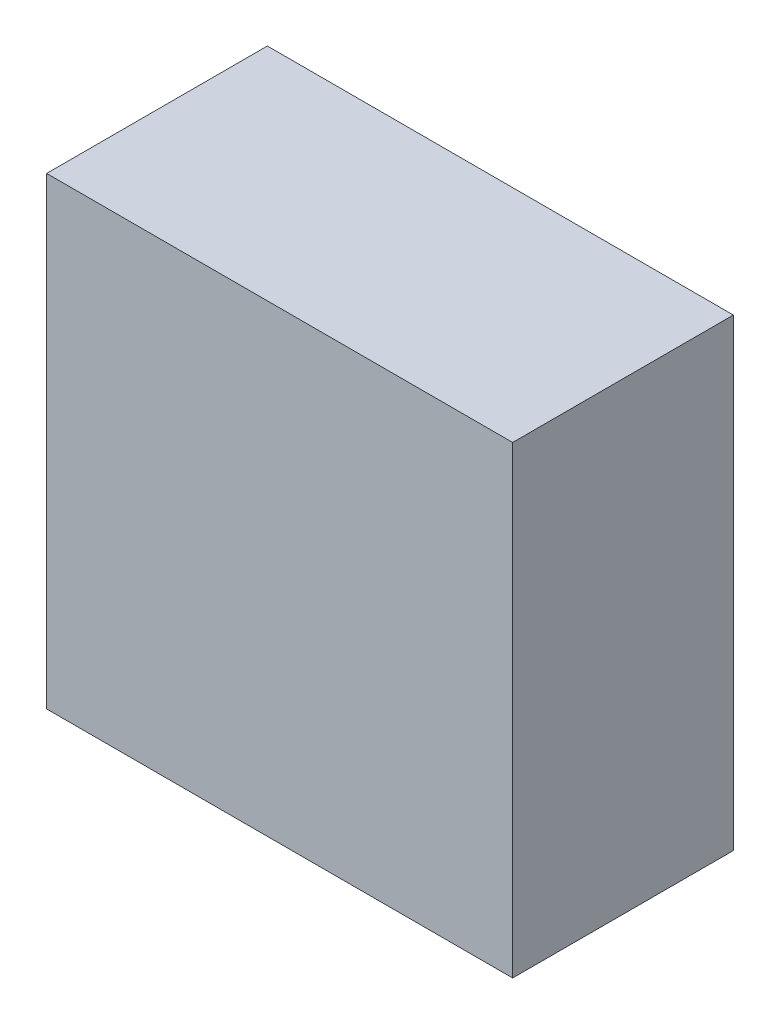
SolidWorks part; units mm, degrees
ref_plane "Front Plane" through (0, 0, 0) normal (0, 0, 1) x (1, 0, 0)
ref_plane "Top Plane" through (0, 0, 0) normal (0, 1, 0) x (1, 0, 0)
ref_plane "Right Plane" through (0, 0, 0) normal (1, 0, 0) x (0, 0, -1)
sketch "Sketch1" plane through (0, 0, 0) normal (0, 0, 1) x (1, 0, 0)
  line L0 (-1.1065, 1) -> (1.005, 1)
  line L1 (1.005, 1) -> (1.005, -1.1016)
  line L2 (1.005, -1.1016) -> (-1.1065, -1.1016)
  line L3 (-1.1065, -1.1016) -> (-1.1065, 1)
extrude "Component_Outline" add sketch "Sketch1" along normal blind 1 separate body
sketch3d "3DSketch1"
  line L0 (0, 0, 0) -> (1, 0, 0)
  line L1 (0, 0, 0) -> (0, 1, 0)
  line L2 (0, 0, 0) -> (0, 0, 1)
  point P0 (0, 0, 0)
